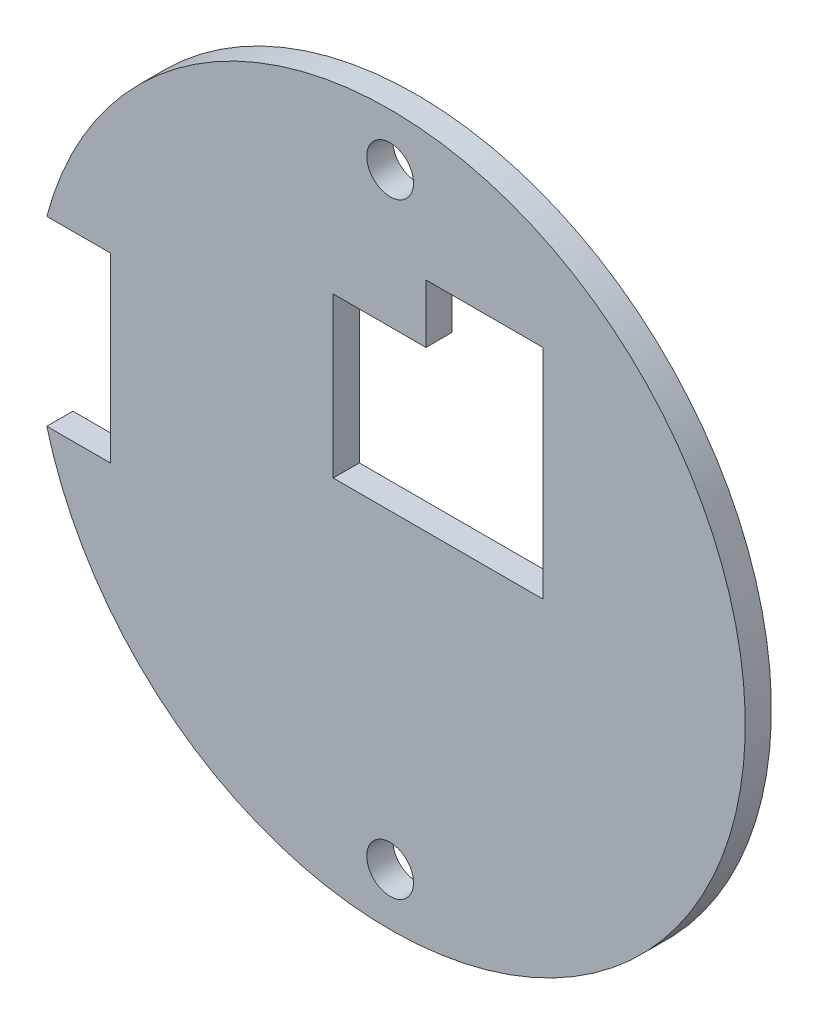
SolidWorks part; units mm, degrees
ref_plane "Front Plane" through (0, 0, 0) normal (0, 0, 1) x (1, 0, 0)
ref_plane "Top Plane" through (0, 0, 0) normal (0, 1, 0) x (1, 0, 0)
ref_plane "Right Plane" through (0, 0, 0) normal (1, 0, 0) x (0, 0, -1)
sketch "Sketch1" plane through (0, 0, 0) normal (0, 0, 1) x (1, 0, 0)
  line L0 (9.2901, 13.7033) -> (2.1781, 13.7033)
  line L1 (2.1781, 13.7033) -> (2.1781, 10.1473)
  line L2 (2.1781, 10.1473) -> (-3.4607, 10.1473)
  line L3 (-3.4607, 10.1473) -> (-3.4607, 0.4572)
  line L4 (-3.4607, 0.4572) -> (9.2901, 0.4572)
  line L5 (9.2901, 0.4572) -> (9.2901, 13.7033)
  line L7 (2.9147, 0.4572) -> (2.9147, -0.8128) construction
  line L9 (-16.9841, 0) -> (0, 0) construction
  line L11 (0, 18.415) -> (0, -18.415) construction
  line L12 (-16.9841, 5.5245) -> (-20.8712, 5.5245) construction
  line L13 (-16.9841, -5.5245) -> (-20.8712, -5.5245) construction
  line L14 (-16.9841, 5.5245) -> (-20.8712, 5.5245)
  line L15 (-16.9841, -5.5245) -> (-20.8712, -5.5245)
  line L16 (-16.9841, 5.5245) -> (-16.9841, -5.5245)
  arc A3 (-20.8712, -5.5245) -> (-20.8712, 5.5245) centre (0, 0) ccw
  circle A4 centre (0, 18.415) radius 1.4224
  circle A5 centre (0, -18.415) radius 1.4224
  dimension "D8" = 2.8448
  dimension "D1" = 0.4572
  dimension "D2" = 13.2461
  dimension "D3" = 12.7508
  dimension "D4" = 3.556
  dimension "D5" = 7.112
  dimension "D10" = 3.4607
extrude "Boss-Extrude1" add sketch "Sketch1" along normal blind 1.5875
